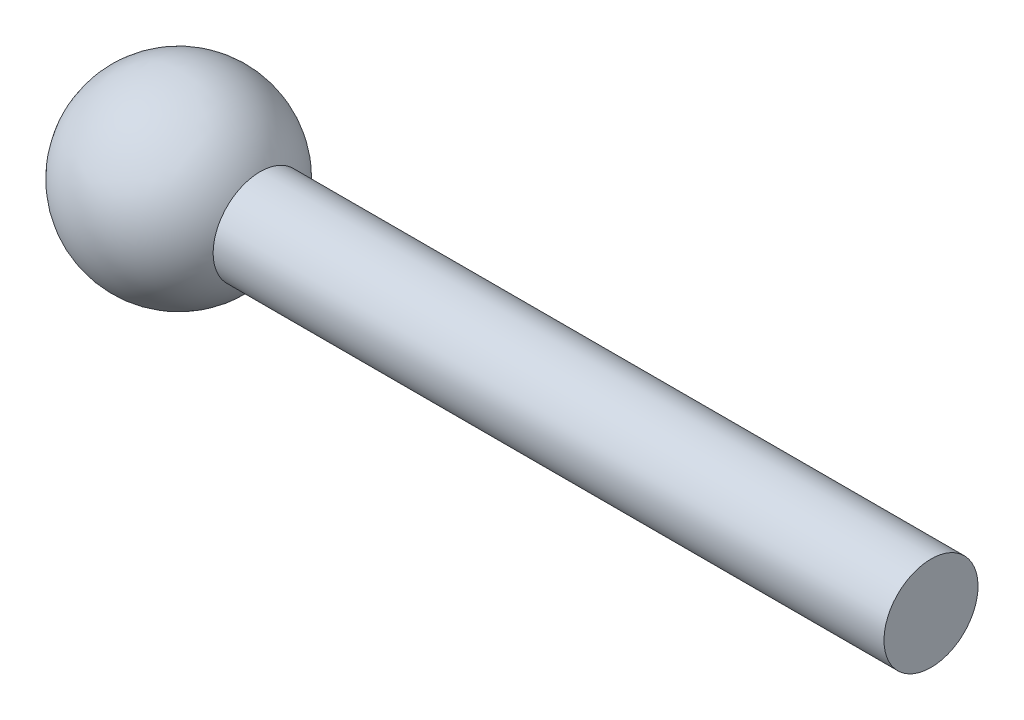
SolidWorks part; units mm, degrees
ref_plane "Front Plane" through (0, 0, 0) normal (0, 0, 1) x (1, 0, 0)
ref_plane "Top Plane" through (0, 0, 0) normal (0, 1, 0) x (1, 0, 0)
ref_plane "Right Plane" through (0, 0, 0) normal (1, 0, 0) x (0, 0, -1)
sketch "Sketch1" plane through (0, 0, 0) normal (0, 0, 1) x (1, 0, 0)
  line L0 (-57.15, -3.175) -> (0, -3.175) construction
  line L1 (0, 0) -> (-45.3007, 0)
  line L2 (0, 0) -> (0, -3.175)
  line L5 (-57.15, -3.175) -> (0, -3.175)
  arc A0 (-45.3007, 0) -> (-57.15, -3.175) centre (-50.8, -3.175) ccw
  dimension "D3" = 12.7
revolve "Revolve1" add sketch "Sketch1" angle 360 about L0
